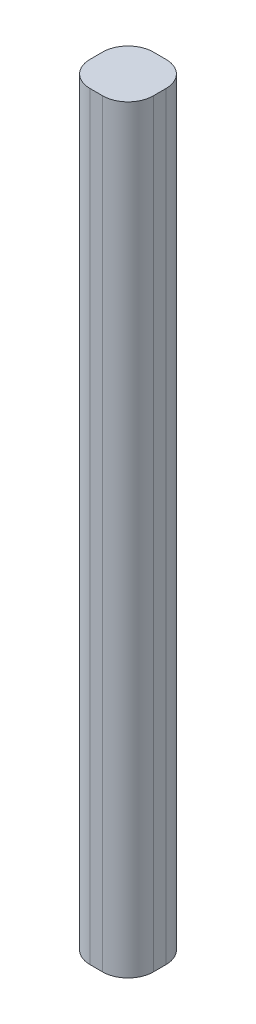
SolidWorks part; units mm, degrees
ref_plane "Front Plane" through (0, 0, 0) normal (0, 0, 1) x (1, 0, 0)
ref_plane "Top Plane" through (0, 0, 0) normal (0, 1, 0) x (1, 0, 0)
ref_plane "Right Plane" through (0, 0, 0) normal (1, 0, 0) x (0, 0, -1)
sketch "Sketch1" plane through (0, 0, 0) normal (0, 1, 0) x (1, 0, 0)
  line L1 (2.5, -2.5) -> (-2.5, -2.5)
  line L2 (2.5, -2.5) -> (2.5, 2.5)
  line L3 (2.5, 2.5) -> (-2.5, 2.5)
  line L4 (-2.5, -2.5) -> (-2.5, 2.5)
  line L5 (2.5, -2.5) -> (-2.5, 2.5) construction
  line L6 (2.5, 2.5) -> (-2.5, -2.5) construction
  point P0 (0, 0)
  dimension "D1" = 5
  dimension "D2" = 5
extrude "Boss-Extrude1" add sketch "Sketch1" along normal blind 60
fillet "Fillet1" radius 2 4 edges at (-2.5, 30, -2.5) (2.5, 30, -2.5) (-2.5, 30, 2.5) (2.5, 30, 2.5)
